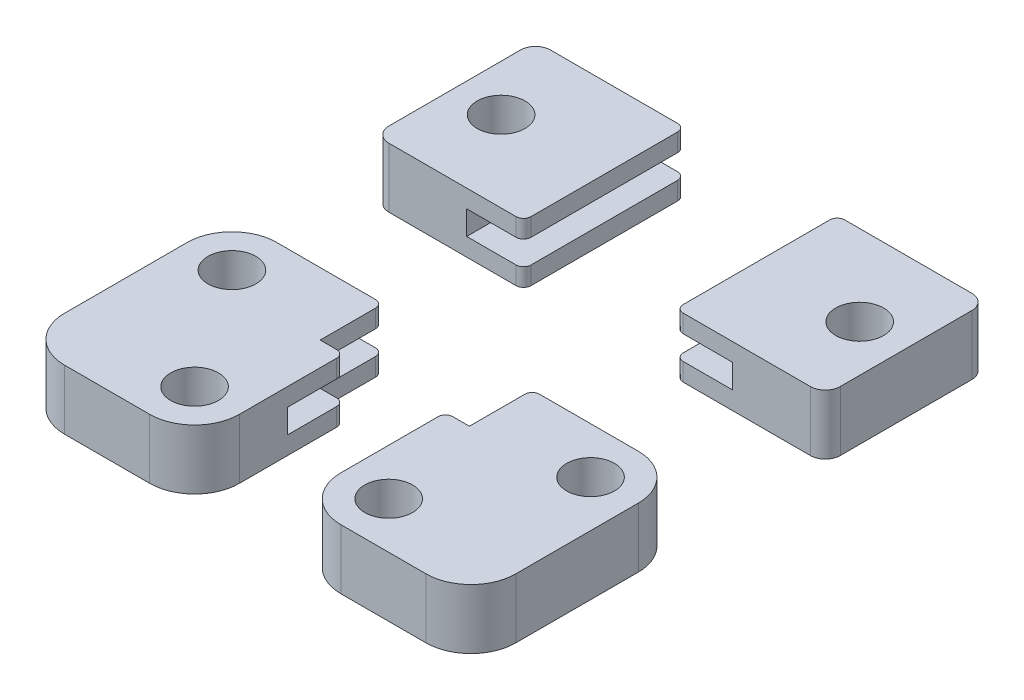
SolidWorks part; units mm, degrees
ref_plane "前视基准面" through (0, 0, 0) normal (0, 0, 1) x (1, 0, 0)
ref_plane "上视基准面" through (0, 0, 0) normal (0, 1, 0) x (1, 0, 0)
ref_plane "右视基准面" through (0, 0, 0) normal (1, 0, 0) x (0, 0, -1)
other "Configuration Table"
sketch "Sketch1" plane through (0, 0, 0) normal (0, 1, 0) x (1, 0, 0)
  line L0 (0, 8) -> (0, 0) construction
  line L1 (0, 0) -> (5.5, 0) construction
  line L2 (5.5, 0) -> (5.5, 3.8)
  line L3 (5.5, 3.8) -> (3.9, 3.8)
  line L4 (3.9, 3.8) -> (3.9, 8)
  line L5 (3.9, 8) -> (0, 8)
  line L6 (0, 8) -> (-6.2, 8)
  line L7 (-6.2, 8) -> (-6.2, -6.2)
  line L8 (-6.2, -6.2) -> (5.5, -6.2)
  line L9 (5.5, -6.2) -> (5.5, 0)
  line L10 (-3.1, 4.9) -> (-3.1, 8) construction
  line L11 (2.4, -3.1) -> (5.5, -3.1) construction
  circle A0 centre (-3.1, 4.9) radius 1.6 construction
  circle A1 centre (2.4, -3.1) radius 1.6 construction
  circle A2 centre (-3.1, 4.9) radius 1
  circle A3 centre (2.4, -3.1) radius 1
  point P16 (0, 0)
  point P19 (0, 0)
  dimension "D5" = 3.2
  dimension "D6" = 2
  dimension "D1" = 5.5
  dimension "D2" = 8
  dimension "D3" = 3.9
  dimension "D4" = 3.8
  dimension "D7" = 1.5
  dimension "D8" = 1.5
extrude "Boss-Extrude1" add sketch "Sketch1" along normal blind 4
sketch "Sketch2" plane through (0, 0, 0) normal (0, -1, 0) x (1, 0, 0)
  line L0 (0, 0) -> (5.5, 0) construction
  line L1 (5.5, -3.8) -> (3.9, -3.8) construction
  line L2 (5.5, 0) -> (5.5, -3.8) construction
  line L3 (3.9, -3.8) -> (3.9, -8) construction
  line L4 (3.9, -8) -> (0, -8) construction
  line L5 (0, -8) -> (0, 0) construction
  line L6 (0, 0) -> (5.5, 0)
  line L7 (5.5, -3.8) -> (3.9, -3.8)
  line L8 (5.5, 0) -> (5.5, -3.8)
  line L9 (3.9, -3.8) -> (3.9, -8)
  line L10 (3.9, -8) -> (0, -8)
  line L11 (0, -8) -> (0, 0)
extrude "Cut-Extrude1" cut sketch "Sketch2" against normal blind 1.6 from offset 1.2 offset against normal yes
sketch "Sketch3" plane through (0, 4, 0) normal (0, 1, 0) x (1, 0, 0)
  circle A0 centre (2.4, -3.1) radius 1.6 construction
  circle A1 centre (-3.1, 4.9) radius 1.6 construction
  circle A2 centre (2.4, -3.1) radius 1.6
  circle A3 centre (-3.1, 4.9) radius 1.6
extrude "Cut-Extrude2" cut sketch "Sketch3" against normal through all
ref_plane "Plane1" through (8.89, 0, 0) normal (1, 0, 0) x (0, 0, -1)
fillet "Fillet1" radius 3 3 edges at (5.5, 2, 6.2) (-6.2, 2, 6.2) (-6.2, 2, -8)
fillet "Fillet2" radius 0.5 4 edges at (5.5, 0.6, -3.8) (5.5, 3.4, -3.8) (3.9, 3.4, -8) (3.9, 0.6, -8)
sketch "Sketch5" plane through (0, 0, 0) normal (0, 1, 0) x (1, 0, 0)
  line L0 (0, 0) -> (5.5, 0) construction
  line L1 (0, 28.3) -> (3.8, 28.3)
  line L2 (0, 28.3) -> (0, 17.5) construction
  line L3 (0, 17.5) -> (3.8, 17.5)
  line L4 (3.8, 28.3) -> (3.8, 17.5)
  line L5 (0, 8) -> (0, 0) construction
  line L6 (0, 28.3) -> (-6.2, 28.3)
  line L7 (-6.2, 28.3) -> (-6.2, 17.5)
  line L8 (-6.2, 17.5) -> (0, 17.5)
  line L9 (-3.1, 22.9) -> (-6.2, 22.9) construction
  line L11 (-6.2, 8) -> (-6.2, -6.2) construction
  circle A0 centre (-3.1, 22.9) radius 1.6 construction
  circle A1 centre (-3.1, 22.9) radius 1
  circle A2 centre (-3.1, 4.9) radius 1 construction
  circle A3 centre (-3.1, 4.9) radius 1.6 construction
  dimension "D1" = 10.8
  dimension "D2" = 28.3
  dimension "D3" = 3.8
extrude "Boss-Extrude2" add sketch "Sketch5" along normal up to surface (4 mm away) separate body up to face at (2.4, 4, 4.7)
sketch "Sketch7" plane through (0, 4, 0) normal (0, 1, 0) x (1, 0, 0)
  circle A1 centre (-3.1, 22.9) radius 1.6 construction
  circle A2 centre (-3.1, 22.9) radius 1.6
extrude "Cut-Extrude4" cut sketch "Sketch7" against normal through all
sketch "Sketch8" plane through (0, 0, 0) normal (0, -1, 0) x (1, 0, 0)
  line L0 (0, -28.3) -> (3.8, -28.3) construction
  line L1 (0, -17.5) -> (3.8, -17.5) construction
  line L2 (3.8, -28.3) -> (3.8, -17.5) construction
  line L3 (0, -28.3) -> (0, -17.5) construction
  line L4 (0, -28.3) -> (3.8, -28.3)
  line L5 (0, -17.5) -> (3.8, -17.5)
  line L6 (3.8, -28.3) -> (3.8, -17.5)
  line L7 (0, -28.3) -> (0, -17.5)
extrude "Cut-Extrude5" cut sketch "Sketch8" against normal up to surface (1.6 mm away) from surface at -1.2 up to face at (3.4259, 2.8, -4.3259) starting at face at (3.4259, 1.2, -4.3259)
fillet "Fillet3" radius 0.5 4 edges at (3.8, 3.4, -28.3) (3.8, 0.6, -28.3) (3.8, 0.6, -17.5) (3.8, 3.4, -17.5)
fillet "Fillet4" radius 1 2 edges at (-6.2, 2, -28.3) (-6.2, 2, -17.5)
mirror "Mirror2" about plane through (8.89, 0, 0) normal (1, 0, 0) of bodies 108 113
sketch "Sketch4" plane through (0, 2.8, 0) normal (0, -1, 0) x (1, 0, 0)
  line L0 (13.88, -3.8) -> (13.88, -2.6)
  line L1 (13.88, -2.6) -> (12.28, -2.6)
  line L6 (12.78, -3.8) -> (13.88, -3.8)
  line L7 (13.88, -3.8) -> (13.88, -7.5)
  line L8 (14.38, -8) -> (17.78, -8)
  line L9 (17.78, -8) -> (17.78, 0)
  line L10 (17.78, 0) -> (12.28, 0)
  line L11 (12.28, 0) -> (12.28, -3.3)
  line L12 (12.78, -3.8) -> (13.88, -3.8)
  line L17 (12.28, -2.6) -> (12.28, -3.3)
  arc A2 (13.88, -7.5) -> (14.38, -8) centre (14.38, -7.5) ccw
  arc A3 (12.28, -3.3) -> (12.78, -3.8) centre (12.78, -3.3) ccw
  arc A5 (12.28, -3.3) -> (12.78, -3.8) centre (12.78, -3.3) ccw
  dimension "D2" = 1.2
  dimension "D1" = 0
extrude "Cut-Extrude3" cut sketch "Sketch4" against normal blind 0.3
